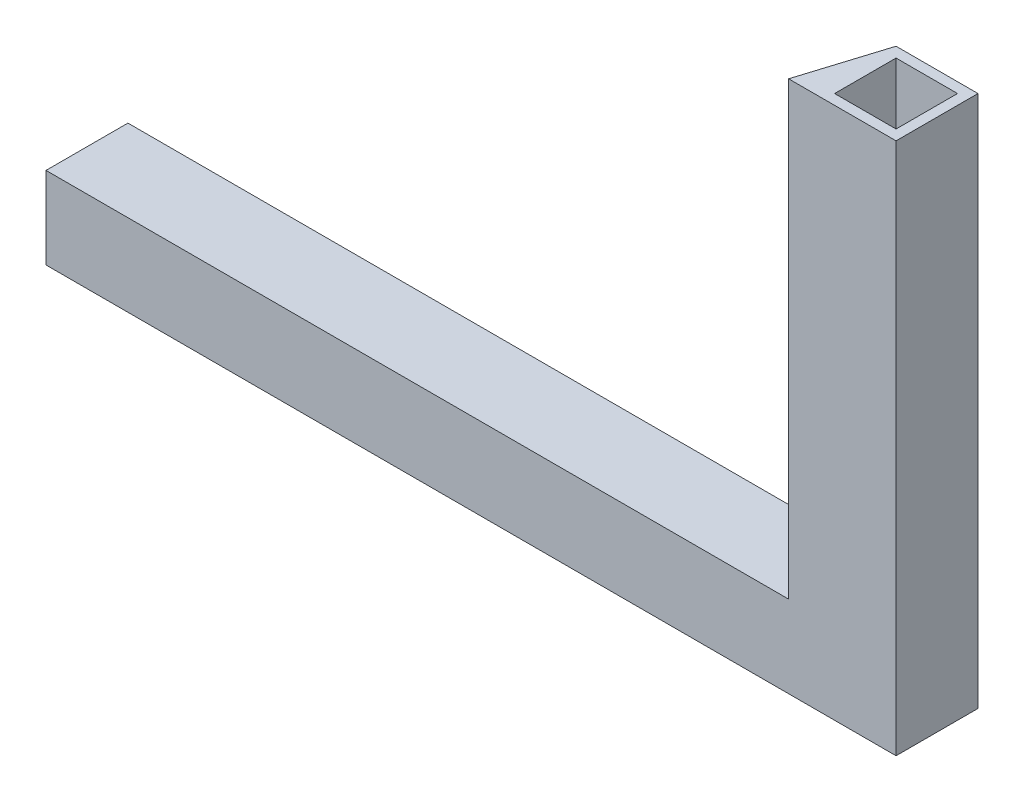
SolidWorks part; units mm, degrees
ref_plane "Plan de face" through (0, 0, 0) normal (0, 0, 1) x (1, 0, 0)
ref_plane "Plan de dessus" through (0, 0, 0) normal (0, 1, 0) x (1, 0, 0)
ref_plane "Plan de droite" through (0, 0, 0) normal (1, 0, 0) x (0, 0, -1)
sketch "Esquisse1" plane through (0, 0, 0) normal (0, 1, 0) x (1, 0, 0)
  line L0 (0, 0) -> (207.5, 0)
  line L1 (207.5, 0) -> (207.5, 20)
  line L2 (207.5, 20) -> (0, 20)
  line L3 (0, 20) -> (0, 0)
  dimension "D1" = 207.5
  dimension "D2" = 20
extrude "Boss.-Extru.1" add sketch "Esquisse1" along normal blind 20
sketch "Esquisse2" plane through (0, 20, 0) normal (0, 1, 0) x (1, 0, 0)
  line L0 (207.5, 20) -> (187.5, 20)
  line L1 (207.5, 20) -> (0, 20) construction
  line L2 (187.5, 20) -> (181.2707, 0)
  line L3 (0, 0) -> (207.5, 0) construction
  line L4 (181.2707, 0) -> (207.5, 0)
  line L5 (207.5, 0) -> (207.5, 20)
  dimension "D1" = 20
  dimension "D2" = 107.3
extrude "Boss.-Extru.2" add sketch "Esquisse2" along normal blind 110
sketch "Esquisse3" plane through (0, 0, 0) normal (-1, 0, 0) x (0, 0, 1)
  line L0 (0, 20) -> (0, 0) construction
  line L1 (-15, 15) -> (-5, 15)
  line L2 (-15, 15) -> (-15, 5)
  line L3 (-15, 5) -> (-5, 5)
  line L4 (-5, 15) -> (-5, 5)
  line L5 (-15, 15) -> (-5, 5) construction
  line L6 (-15, 5) -> (-5, 15) construction
  line L7 (-20, 0) -> (0, 0) construction
  point P0 (-10, 10)
  dimension "D1" = 10
  dimension "D2" = 10
  dimension "D3" = 10
  dimension "D4" = 10
extrude "Enlèv. mat.-Extru.1" cut sketch "Esquisse3" against normal blind 30
hole_wizard "Dégagement M31" positions "Esquisse4" profile "Esquisse5" hole size "M3" standard "Ansi Metric"
sketch "Esquisse4" plane through (0, 0, -20) normal (0, 0, -1) x (-1, 0, 0)
  line L0 (-207.5, 0) -> (0, 0) construction
  line L1 (-207.5, 130) -> (-207.5, 0) construction
  point P0 (-197.5, 80)
  dimension "D1" = 80
  dimension "D2" = 10
sketch "Esquisse5" plane through (197.5, 80, -20) normal (1, 0, 0) x (0, 1, 0)
  line L0 (0, 0) -> (0, 10.9614)
  line L1 (0, 10.9614) -> (1.6, 10)
  line L2 (1.6, 10) -> (1.6, 0)
  line L5 (1.6, 0) -> (0, 0)
  line L10 (0, 10.9614) -> (-1.6, 10) construction
  line L11 (0, -6.35) -> (0, 107.95) construction
  dimension "Diamètre du perçage" = 3.2
  dimension "Profondeur du perçage" = 10
  dimension "Angle de pointe" = 118
sketch "Esquisse6" plane through (0, 130, 0) normal (0, 1, 0) x (1, 0, 0)
  line L0 (207.5, 20) -> (187.5, 20) construction
  line L1 (205, 2.5) -> (190, 2.5)
  line L2 (205, 2.5) -> (205, 17.5)
  line L3 (205, 17.5) -> (190, 17.5)
  line L4 (190, 2.5) -> (190, 17.5)
  line L5 (205, 2.5) -> (190, 17.5) construction
  line L6 (205, 17.5) -> (190, 2.5) construction
  line L7 (207.5, 0) -> (207.5, 20) construction
  point P0 (197.5, 10)
  dimension "D1" = 10
  dimension "D2" = 10
  dimension "D3" = 15
  dimension "D4" = 15
extrude "Enlèv. mat.-Extru.2" cut sketch "Esquisse6" against normal blind 60
